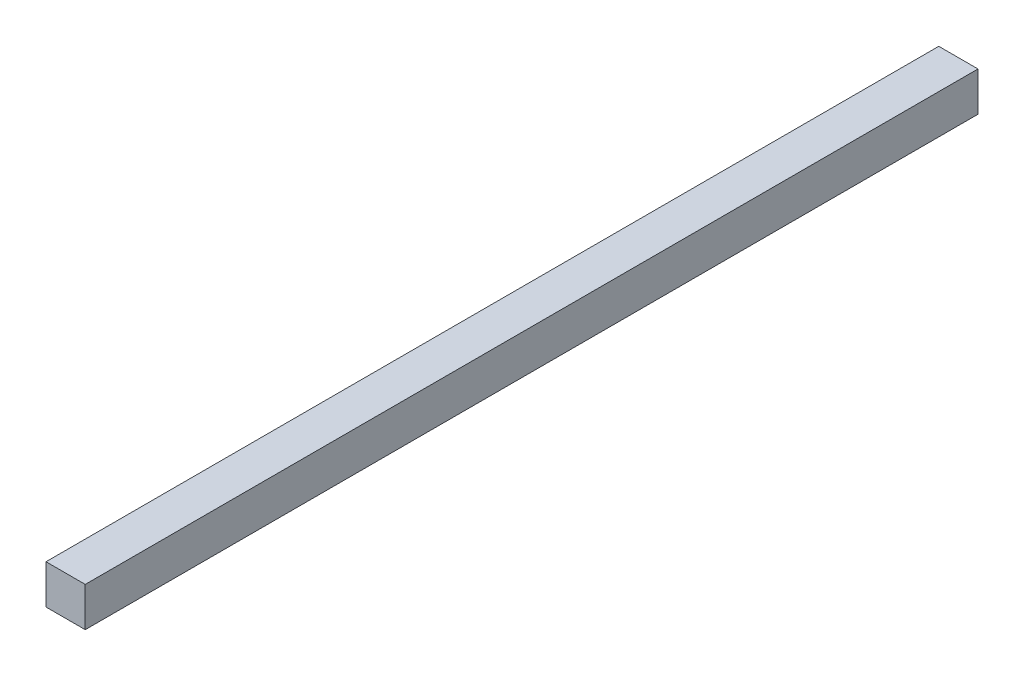
SolidWorks part; units mm, degrees
ref_plane "Front Plane" through (0, 0, 0) normal (0, 0, 1) x (1, 0, 0)
ref_plane "Top Plane" through (0, 0, 0) normal (0, 1, 0) x (1, 0, 0)
ref_plane "Right Plane" through (0, 0, 0) normal (1, 0, 0) x (0, 0, -1)
sketch "Sketch3" plane through (0, 0, 0) normal (0, 0, 1) x (1, 0, 0)
  line L1 (-20, 20) -> (20, 20)
  line L2 (-20, 20) -> (-20, -20)
  line L3 (-20, -20) -> (20, -20)
  line L4 (20, 20) -> (20, -20)
  dimension "D1" = 40
  dimension "D2" = 40
extrude "Boss-Extrude1" add sketch "Sketch3" along normal blind 910
